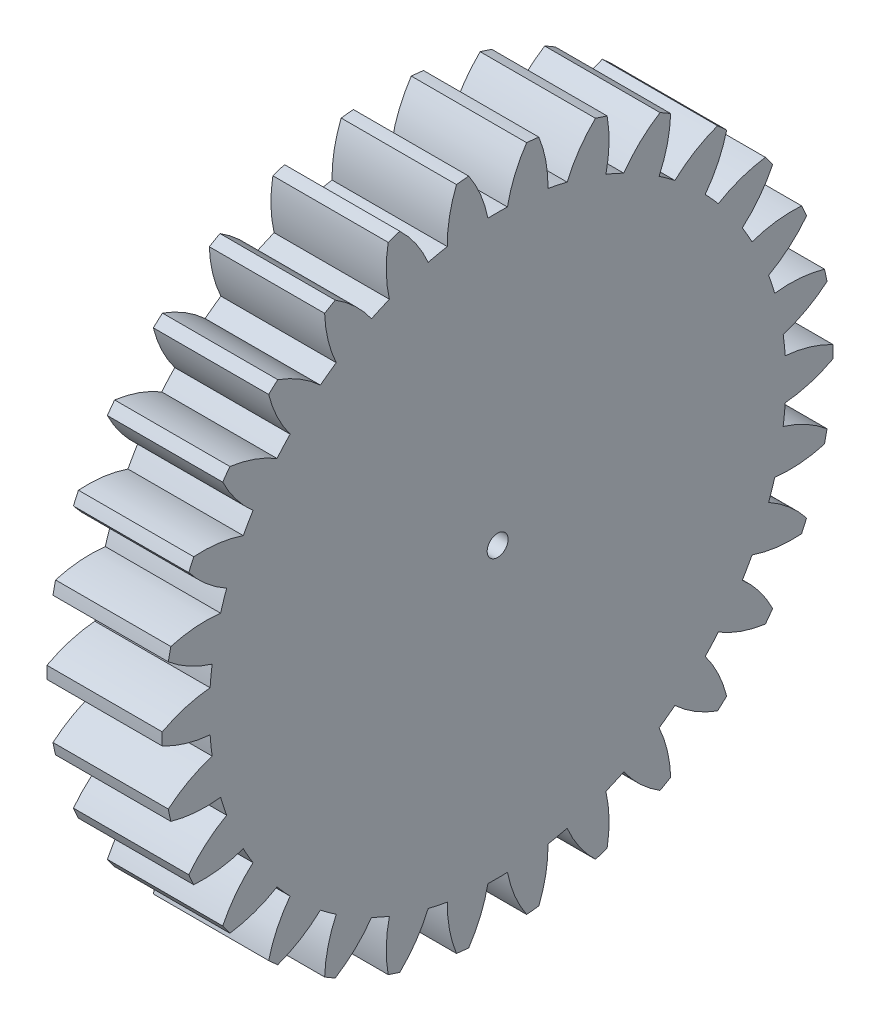
SolidWorks part; units mm, degrees
ref_plane "Plane1" through (0, 0, 0) normal (0, 0, 1) x (1, 0, 0)
ref_plane "Plane2" through (0, 0, 0) normal (0, 1, 0) x (1, 0, 0)
ref_plane "Plane3" through (0, 0, 0) normal (1, 0, 0) x (0, 0, -1)
sketch "HoldingSke" plane through (0, 0, 0) normal (0, 1, 0) x (1, 0, 0)
  line L0 (0, 0) -> (0.866, -0.5)
  line L1 (-15, 0) -> (100, 0) construction
  line L2 (0, 0) -> (-2.1039, 2.3779)
  line L3 (0, 0) -> (-11.863, 4.5341)
  line L4 (0, 0) -> (7.479, 4.318)
  line L5 (0, 0) -> (-46.8476, -17.4728)
  line L6 (0, 0) -> (-4.5593, -3.0762)
  line L7 (-2.1039, 2.3779) -> (8.6586, 51.2059)
  line L8 (-76.2, 54.61) -> (-76.1, 54.61)
  line L9 (-71.009, 38.7566) -> (-53.1078, 45.2721)
  line L10 (-76.2, 71.12) -> (104.1128, 71.12)
  line L11 (0, 0) -> (-5.5, 0)
  line L12 (-76.2, 101.6) -> (-76.162, 101.6)
  line L13 (24.9733, 27.94) -> (52.9518, 28.4284)
  line L14 (24.9733, 27.94) -> (24.9743, 27.94)
  line L15 (24.9733, 27.94) -> (100.4006, 29.5858)
  line L16 (-63.627, -1) -> (-12.827, -1)
  circle A0 centre (0, 0) radius 0.5
  circle A1 centre (0, 0) radius 13.749
  circle A2 centre (0, 0) radius 37.5
  circle A3 centre (0, 0) radius 0.5
  dimension "MHD" = 27.498
  dimension "Hub_dia" = 75
  dimension "Bore" = 1
  dimension "MBD" = 1
  dimension "Num_teeth" = 30
  dimension "Pitch" = 1
  dimension "Overall_len" = 50
  dimension "Show_teeth" = 30
  dimension "Thickness" = 5.5
  dimension "OAL" = 50.0001
  dimension "T_dim" = 0.1
  dimension "Ap" = 20
  dimension "H" = 19.05
  dimension "Pitch_radius" = 180.3128
  dimension "Width" = 5.5
  dimension "Backlash" = 0.038
  dimension "Addendum_fac" = 1
  dimension "Dedendum_fac" = 1.25
  dimension "Clearance_fac" = 0.25
  dimension "Dedendum_add" = 0.001
  dimension "Module" = 1
sketch "BasProSke" plane through (0, 0, 0) normal (0, 1, 0) x (1, 0, 0)
  line L0 (-10, 0) -> (60, 0) construction
  line L1 (0, 0) -> (0, 16)
  line L2 (0, 0) -> (5.5, 0)
  line L3 (5.5, 0) -> (5.5, 16)
  line L4 (5.5, 16) -> (0, 16)
  dimension "Thickness" = 5.5
  dimension "Diameter" = 32
revolve "Base-Revolve" add sketch "BasProSke" angle 360 about L0
sketch "TooCutSke" plane through (0, 0, 0) normal (1, 0, 0) x (0, 0, -1)
  line L1 (0, 0) -> (0, 107) construction
  line L2 (0, 0) -> (-0.8515, 14.9758) construction
  line L3 (0, 0) -> (-3.1323, 29.8014) construction
  line L4 (-0.8515, 14.9758) -> (-1.5661, 14.9007) construction
  arc A0 (0.4664, 13.7411) -> (-0.4664, 13.7411) centre (0, 0) ccw
  arc A1 (1.3975, 15.9644) -> (-1.3975, 15.9644) centre (0, 0) ccw
  circle A2 centre (0, 0) radius 15 construction
  circle A3 centre (0, 0) radius 14.0954 construction
  arc A4 (-0.4664, 13.7411) -> (-1.3975, 15.9644) centre (-6.3534, 12.5823) ccw
  arc A5 (1.3975, 15.9644) -> (0.4664, 13.7411) centre (6.3534, 12.5823) ccw
  dimension "Root_dia" = 27.498
  dimension "Overcut_dia" = 32.0508
  dimension "Pitch_dia" = 30
  dimension "Base_dia" = 28.1908
  dimension "Flank_rad" = 6
  dimension "Half_ang" = 6
  dimension "Half_CT" = 0.7185
extrude "ToothCut" cut sketch "TooCutSke" along normal through all
fillet "Breaks" [suppressed] radius 0.02
fillet "RootFillets" [suppressed] radius 0.251
pattern_circular "TeethCuts" count 30 every 12 about axis through (-10, 0, 0) along (1, 0, 0) of "ToothCut", "RootFillets", "Breaks"
sketch "HubNeaOneSke" plane through (0, 0, 0) normal (-1, 0, 0) x (0, 0, 1)
  circle A0 centre (0, 0) radius 13.749
  dimension "Diameter" = 27.498
extrude "HubNearOne" [suppressed] add sketch "HubNeaOneSke" along normal blind 44.5001
sketch "HubNeaBotSke" plane through (0, 0, 0) normal (-1, 0, 0) x (0, 0, 1)
  circle A0 centre (0, 0) radius 13.749
  dimension "Diameter" = 27.498
extrude "HubNearBoth" [suppressed] add sketch "HubNeaBotSke" along normal blind 22.25
ref_plane "FarPln" through (5.5, 0, 0) normal (1, 0, 0) x (0, 0, -1)
sketch "HubFarSke" plane through (5.5, 0, 0) normal (1, 0, 0) x (0, 0, -1)
  circle A0 centre (0, 0) radius 13.749
  dimension "Diameter" = 27.498
extrude "HubFar" [suppressed] add sketch "HubFarSke" along normal blind 22.25
sketch "BorSke" plane through (0, 0, 0) normal (1, 0, 0) x (0, 0, -1)
  circle A0 centre (0, 0) radius 0.5
  dimension "Diameter" = 1
extrude "Bore" cut sketch "BorSke" along normal mid plane 100.0001
sketch "KeySke" plane through (0, 0, 0) normal (1, 0, 0) x (0, 0, -1)
  line L0 (-0.05, 0) -> (-0.05, 0.6)
  line L1 (-0.05, 0.6) -> (0.05, 0.6)
  line L2 (0.05, 0.6) -> (0.05, 0)
  line L3 (0, 0) -> (0, 34) construction
  line L4 (-0.05, 0) -> (0.05, 0)
  dimension "Offset" = 0.6
  dimension "Width" = 0.1
extrude "Keyway" [suppressed] cut sketch "KeySke" along normal mid plane 100.0001
pattern_circular "Keyway2" [suppressed] count 2 every 90 about axis through (-10, 0, 0) along (1, 0, 0)
equation "' \"Module@HoldingSke\" = 6.35"
equation "' \"Num_teeth@HoldingSke\" = 12"
equation "' \"Ap@HoldingSke\" =  20"
equation "' \"Ap@HoldingSke\" = 20"
equation "' \"Width@HoldingSke\" = 0.5 * 25.4"
equation "' \"Hub_dia@HoldingSke\"= 1 * 25.4"
equation "' \"Hub_dia@HoldingSke\" = 1 * 25.4"
equation "' \"Overall_len@HoldingSke\" = 1.0 * 25.4"
equation "' \"Bore@HoldingSke\" = 0.75 * 25.4"
equation "' \"T_dim@HoldingSke\" = 0.1 * 25.4"
equation "' \"Width@KeySke\" = 0.25 * 25.4"
equation "' \"Show_teeth@HoldingSke\" = 13"
equation "' \"Backlash@HoldingSke\" = 0.009 * 25.4"
equation "' \"Addendum_fac@HoldingSke\" = 1.0"
equation "' \"Dedendum_fac@HoldingSke\" = 1.25"
equation "' \"Dedendum_add@HoldingSke\" = 0.00005 * 25.4"
equation "' \"Clearance_fac@HoldingSke\" = 0.25"
equation "\"Pitch@HoldingSke\" = 1 / \"Module@HoldingSke\""
equation "\"Overcut_dia@TooCutSke\" = (\"Num_teeth@HoldingSke\" + 2 * \"Addendum_fac@HoldingSke\") / \"Pitch@HoldingSke\" + 0.002 * 25.4"
equation "\"Pitch_dia@TooCutSke\" = \"Num_teeth@HoldingSke\" / \"Pitch@HoldingSke\""
equation "\"Base_dia@TooCutSke\" = \"Num_teeth@HoldingSke\" / \"Pitch@HoldingSke\" * cos((\"Ap@HoldingSke\"  * 3.14159265 / 180))"
equation "\"Root_dia@TooCutSke\" = (\"Num_teeth@HoldingSke\" + 2) / \"Pitch@HoldingSke\" - 2 * (\"Addendum_fac@HoldingSke\" + \"Dedendum_fac@HoldingSke\") / \"Pitch@HoldingSke\" - \"Dedendum_add@HoldingSke\" * 2"
equation "\"Half_ang@TooCutSke\" = 180 / \"Num_teeth@HoldingSke\""
equation "\"Half_CT@TooCutSke\" = \"Num_teeth@HoldingSke\" / \"Pitch@HoldingSke\" * sin((3.14159265 / 2 / \"Num_teeth@HoldingSke\")) / 2 - 7 * \"Backlash@HoldingSke\" / 4"
equation "\"Flank_rad@TooCutSke\" = \"Num_teeth@HoldingSke\" / \"Pitch@HoldingSke\" / 5"
equation "\"Radius@RootFillets\" = \"Clearance_fac@HoldingSke\" / \"Pitch@HoldingSke\" + \"Dedendum_add@HoldingSke\""
equation "\"Break_rad@Breaks\" = 0.02 / \"Pitch@HoldingSke\""
equation "\"Thickness@HoldingSke\" = \"Width@HoldingSke\""
equation "\"OAL@HoldingSke\" = \"Thickness@HoldingSke\""
equation "\"MHD@HoldingSke\" = (\"Num_teeth@HoldingSke\" + 2) / \"Pitch@HoldingSke\" - 2 * (\"Addendum_fac@HoldingSke\" + \"Dedendum_fac@HoldingSke\")  / \"Pitch@HoldingSke\" - \"Dedendum_add@HoldingSke\" * 2"
equation "\"MBD@HoldingSke\" = (\"Num_teeth@HoldingSke\" + 2) / \"Pitch@HoldingSke\" - 2 * (\"Addendum_fac@HoldingSke\" + \"Dedendum_fac@HoldingSke\")  / \"Pitch@HoldingSke\" - \"Dedendum_add@HoldingSke\" * 2 - 0.002 * 25.4"
equation "\"MHD@HoldingSke\" = ((sgn( \"MHD@HoldingSke\" - \"Hub_dia@HoldingSke\" )-1)*( \"MHD@HoldingSke\" - \"Hub_dia@HoldingSke\" ))/-2+ \"Hub_dia@HoldingSke\""
equation "\"MBD@HoldingSke\" = ((sgn( \"MBD@HoldingSke\" - \"Bore@HoldingSke\" )-1)*( \"MBD@HoldingSke\" - \"Bore@HoldingSke\" ))/-2+ \"Bore@HoldingSke\""
equation "\"OAL@HoldingSke\" = ((sgn( \"OAL@HoldingSke\" - \"Overall_len@HoldingSke\" )+1)*( \"OAL@HoldingSke\" - \"Overall_len@HoldingSke\" ))/2 + \"Overall_len@HoldingSke\" + 0.000002 * 25.4"
equation "\"Num_teeth@TeethCuts\" = int( \"Show_teeth@HoldingSke\" ) + 1"
equation "\"Num_teeth@TeethCuts\" = ((sgn( \"Num_teeth@TeethCuts\" - \"Num_teeth@HoldingSke\" )-1)*( \"Num_teeth@TeethCuts\" - \"Num_teeth@HoldingSke\" ))/-2+ \"Num_teeth@HoldingSke\""
equation "\"Num_teeth@TeethCuts\" = ((sgn( \"Num_teeth@TeethCuts\" - 2.0)+1)*( \"Num_teeth@TeethCuts\" - 2.0))/2 +2.0"
equation "\"Angle@TeethCuts\" = 360.0 / \"Num_teeth@HoldingSke\""
equation "\"Diameter@BasProSke\" = (\"Num_teeth@HoldingSke\" + 2 * \"Addendum_fac@HoldingSke\") / \"Pitch@HoldingSke\""
equation "\"Thickness@BasProSke\"  = \"Thickness@HoldingSke\""
equation "' \"Fillet_rad@BasProSke\" =  \"Thickness@HoldingSke\" * 0.05"
equation "' \"Fillet_rad@BasProSke\" = \"Thickness@HoldingSke\" * 0.05"
equation "\"MHD@HoldingSke\" = ((sgn( \"MHD@HoldingSke\" - \"Root_dia@TooCutSke\" )-1)*( \"MHD@HoldingSke\" - \"Root_dia@TooCutSke\" ))/-2+ \"Root_dia@TooCutSke\""
equation "\"Diameter@HubNeaOneSke\" = \"MHD@HoldingSke\""
equation "\"Length@HubNearOne\" = \"OAL@HoldingSke\" - \"Thickness@BasProSke\""
equation "\"Diameter@HubNeaBotSke\" = \"MHD@HoldingSke\""
equation "\"Length@HubNearBoth\" = ( \"OAL@HoldingSke\" - \"Thickness@BasProSke\" ) / 2.0"
equation "\"Thickness@FarPln\" = \"Thickness@BasProSke\""
equation "\"Diameter@HubFarSke\" = \"MHD@HoldingSke\""
equation "\"Length@HubFar\" = ( \"OAL@HoldingSke\" - \"Thickness@BasProSke\" ) / 2.0"
equation "\"Diameter@BorSke\" = \"MBD@HoldingSke\""
equation "\"D1@Bore\" = \"OAL@HoldingSke\" * 2.0"
equation "\"D1@Keyway\" = \"OAL@HoldingSke\" * 2.0"
equation "\"Offset@KeySke\" = \"T_dim@HoldingSke\" + \"MBD@HoldingSke\" / 2.0"
